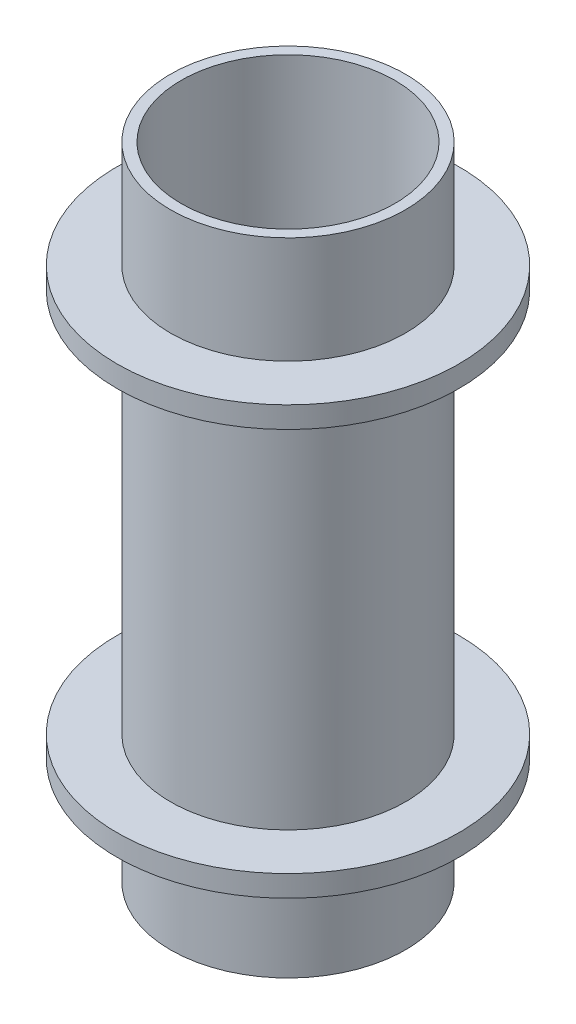
SolidWorks part; units mm, degrees
ref_plane "Спереди" through (0, 0, 0) normal (0, 0, 1) x (1, 0, 0)
ref_plane "Сверху" through (0, 0, 0) normal (0, 1, 0) x (1, 0, 0)
ref_plane "Справа" through (0, 0, 0) normal (1, 0, 0) x (0, 0, -1)
other "Центр тяжести"
sketch "Эскиз1" plane through (0, 0, 0) normal (0, 1, 0) x (1, 0, 0)
  circle A0 centre (0, 0) radius 10
  circle A1 centre (0, 0) radius 11
  dimension "D1" = 20
  dimension "D2" = 22
extrude "Бобышка-Вытянуть1" add sketch "Эскиз1" along normal blind 60
sketch "Эскиз2" plane through (0, 60, 0) normal (0, 1, 0) x (1, 0, 0)
  circle A1 centre (0, 0) radius 16
  circle A3 centre (0, 0) radius 11
  dimension "D1" = 32
extrude "Бобышка-Вытянуть3" add sketch "Эскиз2" against normal blind 2 from offset 10 offset against normal yes
sketch "Эскиз3" plane through (0, 0, 0) normal (0, -1, 0) x (1, 0, 0)
  circle A0 centre (0, 0) radius 11
  circle A1 centre (0, 0) radius 16
extrude "Бобышка-Вытянуть4" add sketch "Эскиз3" against normal blind 2 from offset 10
